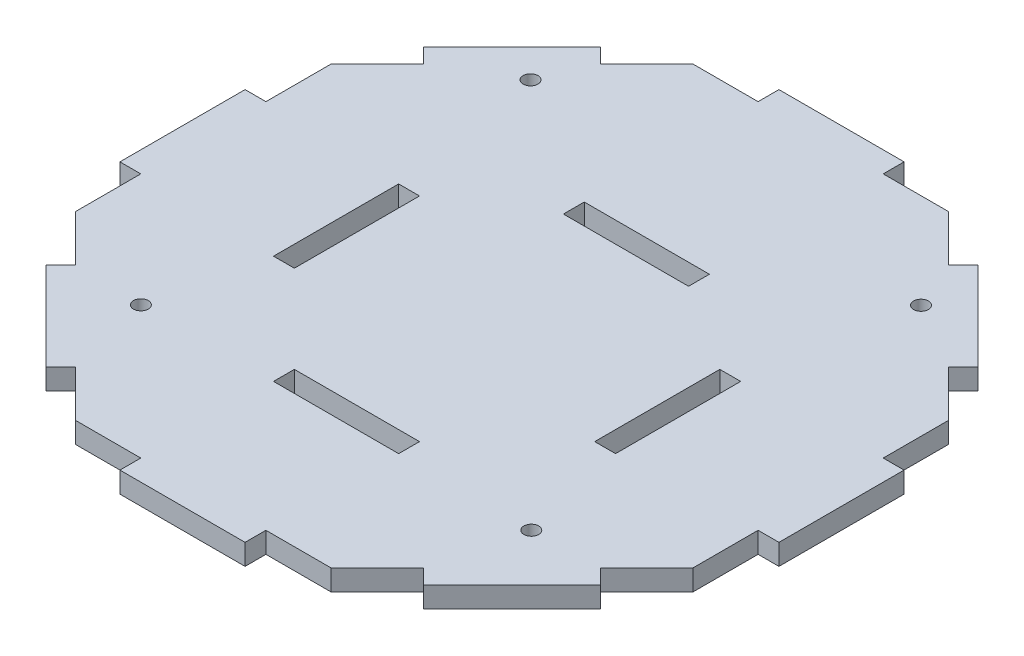
SolidWorks part; units mm, degrees
ref_plane "Front Plane" through (0, 0, 0) normal (0, 0, 1) x (1, 0, 0)
ref_plane "Top Plane" through (0, 0, 0) normal (0, 1, 0) x (1, 0, 0)
ref_plane "Right Plane" through (0, 0, 0) normal (1, 0, 0) x (0, 0, -1)
sketch "Sketch1" plane through (0, 0, 0) normal (0, 1, 0) x (1, 0, 0)
  line L0 (0, 0) -> (46.99, 19.4639) construction
  line L1 (-19.4639, 46.99) -> (-9.525, 46.99)
  line L2 (19.4638, 46.99) -> (26.4917, 39.9622)
  line L3 (26.4917, 39.9622) -> (28.7367, 42.2073)
  line L4 (28.7367, 42.2073) -> (42.2071, 28.7369)
  line L5 (42.2071, 28.7369) -> (39.9621, 26.4918)
  line L6 (39.9621, 26.4918) -> (46.9899, 19.464)
  line L7 (46.9899, 19.464) -> (46.9899, 9.5251)
  line L8 (46.9899, 9.5251) -> (50.1649, 9.5251)
  line L9 (50.1649, 9.5251) -> (50.1649, -9.5249)
  line L10 (-9.525, 46.99) -> (-9.525, 50.165)
  line L11 (-9.525, 50.165) -> (9.525, 50.165)
  line L12 (9.525, 50.165) -> (9.525, 46.99)
  line L13 (0, 50.165) -> (0, 46.99) construction
  line L14 (9.525, 46.99) -> (19.4638, 46.99)
  line L15 (0, 0) -> (16.5622, 0) construction
  line L16 (50.1649, -9.5249) -> (46.99, -9.5249)
  line L17 (46.99, -9.5249) -> (46.99, -19.4637)
  line L18 (46.99, -19.4637) -> (39.9621, -26.4916)
  line L19 (39.9621, -26.4916) -> (42.2072, -28.7367)
  line L20 (42.2072, -28.7367) -> (28.7368, -42.207)
  line L21 (28.7368, -42.207) -> (26.4918, -39.962)
  line L22 (26.4918, -39.962) -> (19.4639, -46.9898)
  line L23 (19.4639, -46.9898) -> (9.525, -46.9898)
  line L24 (9.525, -46.9898) -> (9.525, -50.1648)
  line L25 (9.525, -50.1648) -> (-9.525, -50.1648)
  line L26 (-9.525, -50.1648) -> (-9.525, -46.9899)
  line L27 (-9.525, -46.9899) -> (-19.4638, -46.9899)
  line L28 (-19.4638, -46.9899) -> (-26.4917, -39.962)
  line L29 (-26.4917, -39.962) -> (-28.7367, -42.2071)
  line L30 (-28.7367, -42.2071) -> (-42.2071, -28.7367)
  line L31 (-42.2071, -28.7367) -> (-39.9621, -26.4917)
  line L32 (-39.9621, -26.4917) -> (-46.9899, -19.4638)
  line L33 (-46.9899, -19.4638) -> (-46.9899, -9.525)
  line L34 (-46.9899, -9.525) -> (-50.1649, -9.525)
  line L35 (-50.1649, -9.525) -> (-50.1649, 9.525)
  line L36 (-50.1649, 9.525) -> (-46.9899, 9.525)
  line L37 (-46.9899, 9.525) -> (-46.9899, 19.4639)
  line L38 (-46.9899, 19.4639) -> (-39.9621, 26.4918)
  line L39 (-39.9621, 26.4918) -> (-42.2072, 28.7368)
  line L40 (-42.2072, 28.7368) -> (-28.7368, 42.2072)
  line L41 (-28.7368, 42.2072) -> (-26.4917, 39.9622)
  line L42 (-26.4917, 39.9622) -> (-19.4639, 46.99)
  circle A0 centre (0, 0) radius 46.99 construction
  point P58 (0, 0.0001)
  dimension "D1" = 8
  dimension "D3" = 3.175
  dimension "D7" = 3.175
  dimension "D8" = 93.98
  dimension "D2" = 22.5
  dimension "D4" = 19.05
  dimension "D5" = 38.9277
extrude "Boss-Extrude1" add sketch "Sketch1" along normal blind 3.175
hole_wizard "#2 Clearance Hole1" positions "Sketch3" profile "Sketch2" hole size "#2" standard "ANSI Inch" end condition through all
sketch "Sketch3" plane through (0, 3.175, 0) normal (0, 1, 0) x (1, 0, 0)
  line L0 (-29.718, -26.7813) -> (29.718, -26.7813) construction
  line L2 (-29.718, 32.541) -> (29.718, 32.541) construction
  line L4 (29.718, -26.7813) -> (34.9069, -31.4575) construction
  line L6 (-29.718, -26.7813) -> (-34.9069, -31.4575) construction
  line L7 (-34.9069, -31.4575) -> (-21.3739, -46.4743) construction
  line L9 (34.9069, -31.4575) -> (19.2705, -48.8084) construction
  line L10 (-31.6878, 34.6979) -> (-29.718, 32.541) construction
  line L11 (29.718, 32.541) -> (31.6878, 34.6979) construction
  line L12 (31.6878, 34.6979) -> (17.8834, 47.3047) construction
  line L14 (-31.6878, 34.6979) -> (-23.5062, 42.1697) construction
  circle A1 centre (0, 0) radius 46.99 construction
  point P0 (-29.718, -26.7813)
  point P2 (-29.718, 32.541)
  point P4 (29.718, 32.541)
  point P6 (29.718, -26.7813)
  dimension "D1" = 2.921
  dimension "D2" = 59.436
  dimension "D3" = 6.985
sketch "Sketch2" plane through (-29.718, 3.175, 26.7813) normal (1, 0, 0) x (0, 0, 1)
  line L0 (0, 0) -> (0, 3.175)
  line L1 (0, 3.175) -> (1.1303, 3.175)
  line L2 (1.1303, 3.175) -> (1.1303, 0)
  line L5 (1.1303, 0) -> (0, 0)
  line L11 (0, -6.35) -> (0, 107.95) construction
  dimension "Thru Hole Dia." = 2.2606
  dimension "Thru Hole Depth" = 3.175
sketch "Sketch4" plane through (0, 3.175, 0) normal (0, 1, 0) x (1, 0, 0)
  line L0 (-29.718, -26.7813) -> (29.718, -26.7813) construction
  line L1 (26.035, 20.5262) -> (26.035, -26.7813) construction
  line L2 (26.035, -26.7813) -> (-26.035, -26.7813) construction
  line L3 (-26.035, -26.7813) -> (-26.035, 20.5262) construction
  line L4 (29.718, -26.7813) -> (26.035, -26.7813) construction
  line L5 (-26.035, -26.7813) -> (-29.718, -26.7813) construction
  line L6 (-22.86, -10.2713) -> (-26.035, -10.2713)
  line L7 (-22.86, -10.2713) -> (-22.86, 8.7787)
  line L8 (-22.86, 8.7787) -> (-26.035, 8.7787)
  line L9 (-26.035, -10.2713) -> (-26.035, 8.7787)
  line L10 (26.035, -10.2713) -> (22.86, -10.2713)
  line L11 (26.035, -10.2713) -> (26.035, 8.7787)
  line L12 (26.035, 8.7787) -> (22.86, 8.7787)
  line L13 (22.86, -10.2713) -> (22.86, 8.7787)
  line L14 (9.525, 17.3512) -> (-9.525, 17.3512)
  line L15 (9.525, 17.3512) -> (9.525, 20.5262)
  line L16 (9.525, 20.5262) -> (-9.525, 20.5262)
  line L17 (-9.525, 17.3512) -> (-9.525, 20.5262)
  line L18 (26.035, 20.5262) -> (-26.035, 20.5262) construction
  line L19 (0, -23.6063) -> (0, -26.7813) construction
  line L20 (9.525, -26.7813) -> (-9.525, -26.7813)
  line L21 (9.525, -26.7813) -> (9.525, -23.6063)
  line L22 (9.525, -23.6063) -> (-9.525, -23.6063)
  line L23 (-9.525, -26.7813) -> (-9.525, -23.6063)
  line L25 (0, 17.3512) -> (0, 20.5262) construction
  dimension "D1" = 52.07
  dimension "D2" = 47.3075
  dimension "D3" = 3.175
  dimension "D4" = 19.05
  dimension "D5" = 16.51
extrude "Cut-Extrude1" cut sketch "Sketch4" against normal through all
